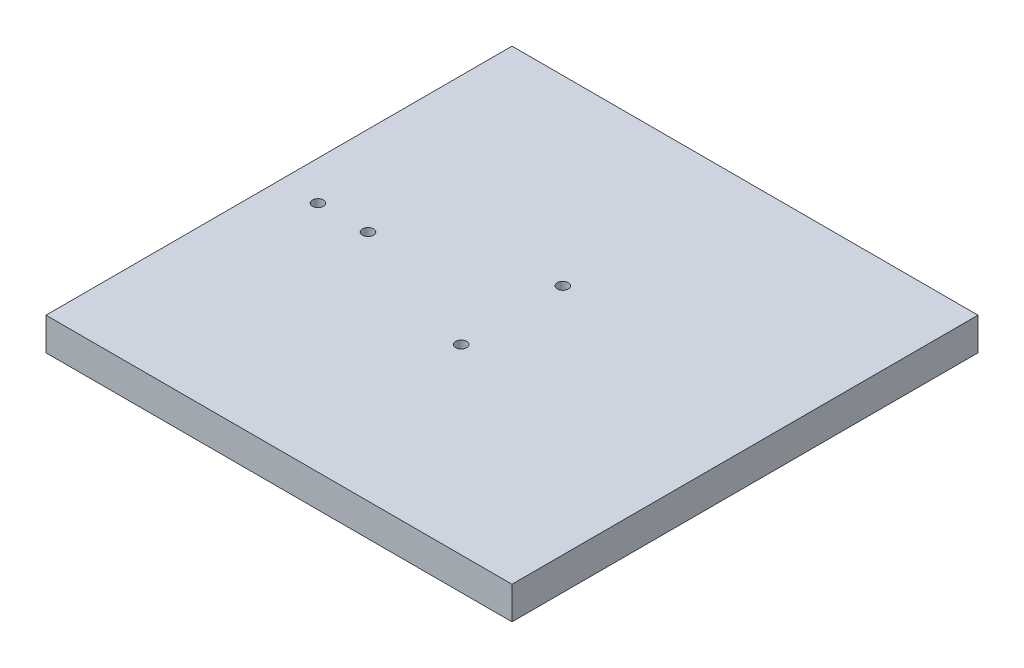
SolidWorks part; units mm, degrees
material "Maple"
ref_plane "Front Plane" through (0, 0, 0) normal (0, 0, 1) x (1, 0, 0)
ref_plane "Top Plane" through (0, 0, 0) normal (0, 1, 0) x (1, 0, 0)
ref_plane "Right Plane" through (0, 0, 0) normal (1, 0, 0) x (0, 0, -1)
sketch "Sketch1" plane through (0, 0, 0) normal (0, 0, 1) x (1, 0, 0)
  line L1 (0, 0) -> (139.7, 0)
  line L2 (0, 0) -> (0, 9.779)
  line L3 (0, 9.779) -> (139.7, 9.779)
  line L4 (139.7, 0) -> (139.7, 9.779)
  dimension "D1" = 9.779
  dimension "D2" = 139.7
extrude "Boss-Extrude1" add sketch "Sketch1" along normal blind 139.7
sketch "Sketch2" plane through (0, 9.779, 0) normal (0, 1, 0) x (1, 0, 0)
  line L0 (0, -69.85) -> (11.684, -69.85)
  line L1 (0, -139.7) -> (0, 0) construction
  line L2 (11.684, -69.85) -> (26.684, -69.85)
  circle A0 centre (11.684, -69.85) radius 1.65
  circle A1 centre (26.684, -69.85) radius 1.65
  dimension "D3" = 3.3
  dimension "D4" = 3.3
  dimension "D1" = 11.684
  dimension "D2" = 15
extrude "Cut-Extrude1" cut sketch "Sketch2" against normal through all
sketch "Sketch3" plane through (0, 9.779, 0) normal (0, 1, 0) x (1, 0, 0)
  line L0 (69.85, 0) -> (69.85, -139.7)
  line L1 (139.7, 0) -> (0, 0) construction
  line L2 (139.7, -139.7) -> (0, -139.7) construction
  line L3 (69.85, -85.09) -> (69.85, -54.61)
  circle A0 centre (69.85, -54.61) radius 1.65
  circle A1 centre (69.85, -85.09) radius 1.65
  point P9 (69.85, -69.85)
  dimension "D2" = 3.3
  dimension "D3" = 3.3
  dimension "D1" = 30.48
extrude "Cut-Extrude2" cut sketch "Sketch3" against normal through all contours L0 A0 | L0 A0 | L0 A1 | L0 A1
